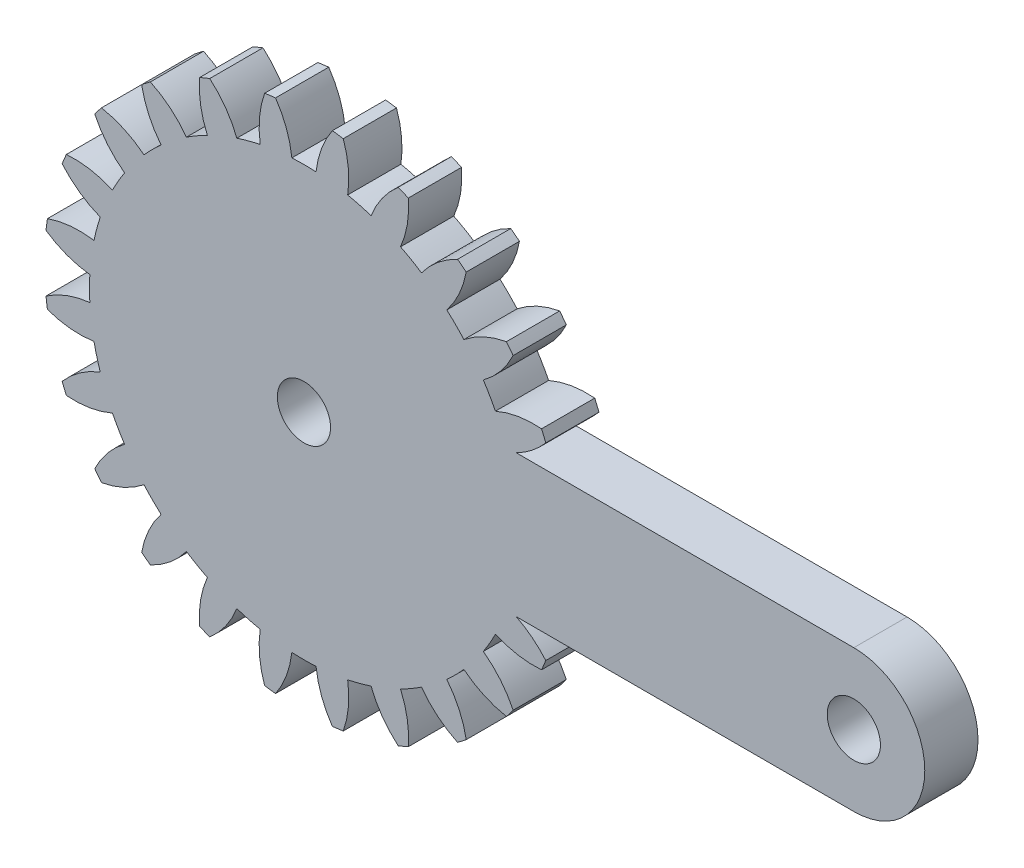
SolidWorks part; units mm, degrees
ref_plane "Front Plane" through (0, 0, 0) normal (0, 0, 1) x (1, 0, 0)
ref_plane "Top Plane" through (0, 0, 0) normal (0, 1, 0) x (1, 0, 0)
ref_plane "Right Plane" through (0, 0, 0) normal (1, 0, 0) x (0, 0, -1)
sketch "Sketch1" plane through (0, 0, 0) normal (0, 0, 1) x (1, 0, 0)
  line L0 (0, 18.4198) -> (0, -12.09) construction
  line L1 (-19.3129, 0) -> (17.8594, 0) construction
  line L2 (0, 0) -> (-0.5167, 3.9247) construction
  line L3 (0, 0) -> (0.5167, 3.9247) construction
  line L4 (31, 4) -> (11.968, 4)
  line L5 (31, -4) -> (11.968, -4)
  line L6 (0, 0) -> (-0.6821, 12.0707) construction
  line L7 (0, 0) -> (0.8332, 4) construction
  line L8 (0, 0) -> (-0.6821, 12.0707) construction
  line L9 (0, 0) -> (-3.783, 11.4829) construction
  line L10 (1.5781, 11.9866) -> (2.3463, 17.822) construction
  line L11 (-1.5781, 11.9866) -> (-2.3403, 17.776) construction
  line L12 (0, -14.63) -> (0, -17.9711) construction
  arc A0 (3.783, 11.4829) -> (2.4653, 11.836) centre (0, 0) ccw
  arc A1 (-11.4155, 9.1501) -> (-11.7929, 8.6583) centre (0, 0) ccw
  arc A2 (31, -4) -> (31, 4) centre (31, 0) ccw
  circle A3 centre (31, 0) radius 1.5
  circle A4 centre (0, 0) radius 1.5
  arc A5 (-2.2165, 14.4611) -> (-2.4653, 11.836) centre (2.8723, 12.6545) ccw
  arc A6 (-1.6018, 14.542) -> (-0.6821, 12.0707) centre (-6.0497, 11.4799) cw
  arc A7 (2.2165, 14.4611) -> (2.4653, 11.836) centre (-2.8723, 12.6545) cw
  arc A8 (1.6018, 14.542) -> (0.6821, 12.0707) centre (6.0497, 11.4799) ccw
  arc A9 (2.2165, 14.4611) -> (2.4653, 11.836) centre (-2.8723, 12.6545) cw
  arc A10 (1.6018, 14.542) -> (0.6821, 12.0707) centre (6.0497, 11.4799) ccw
  arc A11 (5.8838, 13.3947) -> (5.4447, 10.7946) centre (0.5008, 12.9667) cw
  arc A12 (5.311, 13.6319) -> (3.783, 11.4829) centre (8.8147, 9.5229) ccw
  arc A13 (9.1501, 11.4155) -> (8.053, 9.0176) centre (3.8397, 12.3953) cw
  arc A14 (8.6583, 11.7929) -> (6.6261, 10.1125) centre (10.9791, 6.917) ccw
  arc A15 (11.7929, 8.6583) -> (10.1125, 6.6261) centre (6.917, 10.9791) cw
  arc A16 (11.4155, 9.1501) -> (9.0176, 8.053) centre (12.3953, 3.8397) ccw
  arc A17 (13.6319, 5.311) -> (11.968, 4) centre (9.5229, 8.8147) cw
  arc A18 (13.3947, 5.8838) -> (10.7946, 5.4447) centre (12.9667, 0.5008) ccw
  arc A19 (-5.311, 13.6319) -> (-3.783, 11.4829) centre (-8.8147, 9.5229) cw
  arc A20 (-5.8838, 13.3947) -> (-5.4447, 10.7946) centre (-0.5008, 12.9667) ccw
  arc A21 (-8.6583, 11.7929) -> (-6.6261, 10.1125) centre (-10.9791, 6.917) cw
  arc A22 (-9.1501, 11.4155) -> (-8.053, 9.0176) centre (-3.8397, 12.3953) ccw
  arc A23 (-11.4155, 9.1501) -> (-9.0176, 8.053) centre (-12.3953, 3.8397) cw
  arc A24 (-11.7929, 8.6583) -> (-10.1125, 6.6261) centre (-6.917, 10.9791) ccw
  arc A25 (-13.3947, 5.8838) -> (-10.7946, 5.4447) centre (-12.9667, 0.5008) cw
  arc A26 (-13.6319, 5.311) -> (-11.4829, 3.783) centre (-9.5229, 8.8147) ccw
  arc A27 (-14.4611, 2.2165) -> (-11.836, 2.4653) centre (-12.6545, -2.8723) cw
  arc A28 (-14.542, 1.6018) -> (-12.0707, 0.6821) centre (-11.4799, 6.0497) ccw
  arc A29 (-14.542, -1.6018) -> (-12.0707, -0.6821) centre (-11.4799, -6.0497) cw
  arc A30 (-14.4611, -2.2165) -> (-11.836, -2.4653) centre (-12.6545, 2.8723) ccw
  arc A31 (-13.6319, -5.311) -> (-11.4829, -3.783) centre (-9.5229, -8.8147) cw
  arc A32 (-13.3947, -5.8838) -> (-10.7946, -5.4447) centre (-12.9667, -0.5008) ccw
  arc A33 (-11.7929, -8.6583) -> (-10.1125, -6.6261) centre (-6.917, -10.9791) cw
  arc A34 (-11.4155, -9.1501) -> (-9.0176, -8.053) centre (-12.3953, -3.8397) ccw
  arc A35 (-9.1501, -11.4155) -> (-8.053, -9.0176) centre (-3.8397, -12.3953) cw
  arc A36 (-8.6583, -11.7929) -> (-6.6261, -10.1125) centre (-10.9791, -6.917) ccw
  arc A37 (-5.8838, -13.3947) -> (-5.4447, -10.7946) centre (-0.5008, -12.9667) cw
  arc A38 (-5.311, -13.6319) -> (-3.783, -11.4829) centre (-8.8147, -9.5229) ccw
  arc A39 (-2.2165, -14.4611) -> (-2.4653, -11.836) centre (2.8723, -12.6545) cw
  arc A40 (-1.6018, -14.542) -> (-0.6821, -12.0707) centre (-6.0497, -11.4799) ccw
  arc A41 (1.6018, -14.542) -> (0.6821, -12.0707) centre (6.0497, -11.4799) cw
  arc A42 (2.2165, -14.4611) -> (2.4653, -11.836) centre (-2.8723, -12.6545) ccw
  arc A43 (5.311, -13.6319) -> (3.783, -11.4829) centre (8.8147, -9.5229) cw
  arc A44 (5.8838, -13.3947) -> (5.4447, -10.7946) centre (0.5008, -12.9667) ccw
  arc A45 (8.6583, -11.7929) -> (6.6261, -10.1125) centre (10.9791, -6.917) cw
  arc A46 (9.1501, -11.4155) -> (8.053, -9.0176) centre (3.8397, -12.3953) ccw
  arc A47 (11.4155, -9.1501) -> (9.0176, -8.053) centre (12.3953, -3.8397) cw
  arc A48 (11.7929, -8.6583) -> (10.1125, -6.6261) centre (6.917, -10.9791) ccw
  arc A49 (13.3947, -5.8838) -> (10.7946, -5.4447) centre (12.9667, -0.5008) cw
  arc A50 (13.6319, -5.311) -> (11.968, -4) centre (9.5229, -8.8147) ccw
  arc A51 (-8.6583, 11.7929) -> (-9.1501, 11.4155) centre (0, 0) ccw
  arc A52 (-13.3947, 5.8838) -> (-13.6319, 5.311) centre (0, 0) ccw
  arc A53 (-14.4611, 2.2165) -> (-14.542, 1.6018) centre (0, 0) ccw
  arc A54 (-14.542, -1.6018) -> (-14.4611, -2.2165) centre (0, 0) ccw
  arc A55 (0.6821, 12.0707) -> (-0.6821, 12.0707) centre (0, 0) ccw
  arc A56 (-5.4447, 10.7946) -> (-6.6261, 10.1125) centre (0, 0) ccw
  arc A57 (-8.053, 9.0176) -> (-9.0176, 8.053) centre (0, 0) ccw
  arc A58 (-10.1125, 6.6261) -> (-10.7946, 5.4447) centre (0, 0) ccw
  arc A59 (-11.4829, 3.783) -> (-11.836, 2.4653) centre (0, 0) ccw
  arc A60 (-2.4653, 11.836) -> (-3.783, 11.4829) centre (0, 0) ccw
  arc A61 (6.6261, 10.1125) -> (5.4447, 10.7946) centre (0, 0) ccw
  arc A62 (9.0176, 8.053) -> (8.053, 9.0176) centre (0, 0) ccw
  arc A63 (10.7946, 5.4447) -> (10.1125, 6.6261) centre (0, 0) ccw
  arc A64 (-13.6319, -5.311) -> (-13.3947, -5.8838) centre (0, 0) ccw
  arc A65 (10.1125, -6.6261) -> (10.7946, -5.4447) centre (0, 0) ccw
  arc A66 (8.053, -9.0176) -> (9.0176, -8.053) centre (0, 0) ccw
  arc A67 (5.4447, -10.7946) -> (6.6261, -10.1125) centre (0, 0) ccw
  arc A68 (2.4653, -11.836) -> (3.783, -11.4829) centre (0, 0) ccw
  arc A69 (-0.6821, -12.0707) -> (0.6821, -12.0707) centre (0, 0) ccw
  arc A70 (-3.783, -11.4829) -> (-2.4653, -11.836) centre (0, 0) ccw
  arc A71 (-12.0707, 0.6821) -> (-12.0707, -0.6821) centre (0, 0) ccw
  arc A72 (-11.836, -2.4653) -> (-11.4829, -3.783) centre (0, 0) ccw
  arc A73 (-9.0176, -8.053) -> (-8.053, -9.0176) centre (0, 0) ccw
  arc A74 (-6.6261, -10.1125) -> (-5.4447, -10.7946) centre (0, 0) ccw
  arc A75 (-11.7929, -8.6583) -> (-11.4155, -9.1501) centre (0, 0) ccw
  arc A76 (-9.1501, -11.4155) -> (-8.6583, -11.7929) centre (0, 0) ccw
  arc A77 (-5.8838, -13.3947) -> (-5.311, -13.6319) centre (0, 0) ccw
  arc A78 (-2.2165, -14.4611) -> (-1.6018, -14.542) centre (0, 0) ccw
  arc A79 (1.6018, -14.542) -> (2.2165, -14.4611) centre (0, 0) ccw
  arc A80 (5.311, -13.6319) -> (5.8838, -13.3947) centre (0, 0) ccw
  arc A81 (8.6583, -11.7929) -> (9.1501, -11.4155) centre (0, 0) ccw
  arc A82 (11.4155, -9.1501) -> (11.7929, -8.6583) centre (0, 0) ccw
  arc A83 (13.3947, -5.8838) -> (13.6319, -5.311) centre (0, 0) ccw
  arc A84 (-10.7946, -5.4447) -> (-10.1125, -6.6261) centre (0, 0) ccw
  arc A85 (13.6319, 5.311) -> (13.3947, 5.8838) centre (0, 0) ccw
  arc A86 (11.7929, 8.6583) -> (11.4155, 9.1501) centre (0, 0) ccw
  arc A87 (9.1501, 11.4155) -> (8.6583, 11.7929) centre (0, 0) ccw
  arc A88 (5.8838, 13.3947) -> (5.311, 13.6319) centre (0, 0) ccw
  arc A89 (2.2165, 14.4611) -> (-5.8838, 13.3947) centre (0, 0) ccw
  point P21 (-1.9096, 14.5048)
  point P24 (-1.5781, 11.9866)
  point P25 (-1.9095, 14.5038)
  dimension "D1" = 29.26
  dimension "D2" = 24.18
  dimension "D5" = 8
  dimension "D7" = 3
  dimension "D14" = 5.4
  dimension "D3" = 15
  dimension "D4" = 7.5
  dimension "D6" = 31
  dimension "D8" = 0.62
  dimension "D9" = 1.7986
  dimension "D11" = 15
  dimension "D13" = 15
  dimension "D10" = 6
  dimension "D12" = 17
extrude "Boss-Extrude1" add sketch "Sketch1" against normal blind 3 contours A7 A89 A8 A55 A6 A5 A60 A19 A20 A56 A21 A51 A22 A57 A23 A1 A24 A58 A25 A52 A26 A59 A27 A53 A28 A71 A29 A54 A30 A72 A33 A75 A34 A73 A35 A76 A36 A74 A37 A77 A38 A70 A39 A78 A40 A69 A41
scale "Scale1" scale about centroid uniform scaling yes scale factor 1.9
